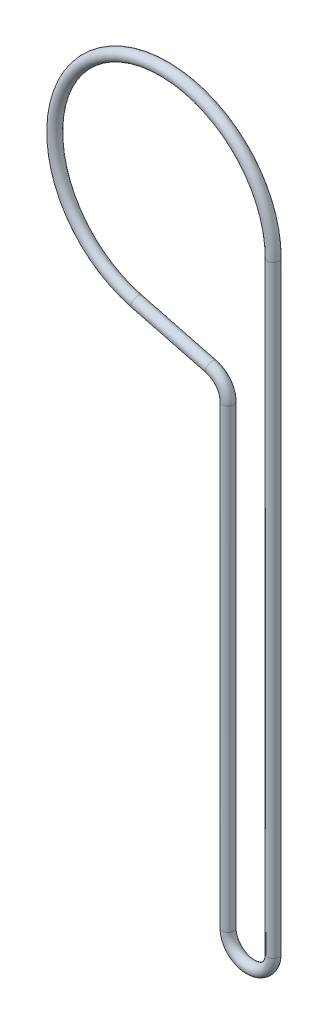
SolidWorks part; units mm, degrees
ref_plane "Front" through (0, 0, 0) normal (0, 0, 1) x (1, 0, 0)
ref_plane "Top" through (0, 0, 0) normal (0, 1, 0) x (1, 0, 0)
ref_plane "Right" through (0, 0, 0) normal (1, 0, 0) x (0, 0, -1)
sketch "Esquisse1" plane through (0, 0, 0) normal (0, 0, 1) x (1, 0, 0)
  line L0 (29, 0) -> (29, -160)
  line L1 (17, -160) -> (17, -39)
  line L2 (12.5033, -33.1914) -> (-7.2659, -28.075)
  arc A0 (29, 0) -> (-7.2659, -28.075) centre (0, 0) ccw
  arc A1 (29, -160) -> (17, -160) centre (23, -160) cw
  arc A2 (17, -39) -> (12.5033, -33.1914) centre (11, -39) ccw
  dimension "D1" = 29
  dimension "D2" = 160
  dimension "D3" = 6
  dimension "D4" = 39
sweep "Balayage1" add path "Esquisse1" circular profile diameter 3 parameters "D3"=3
